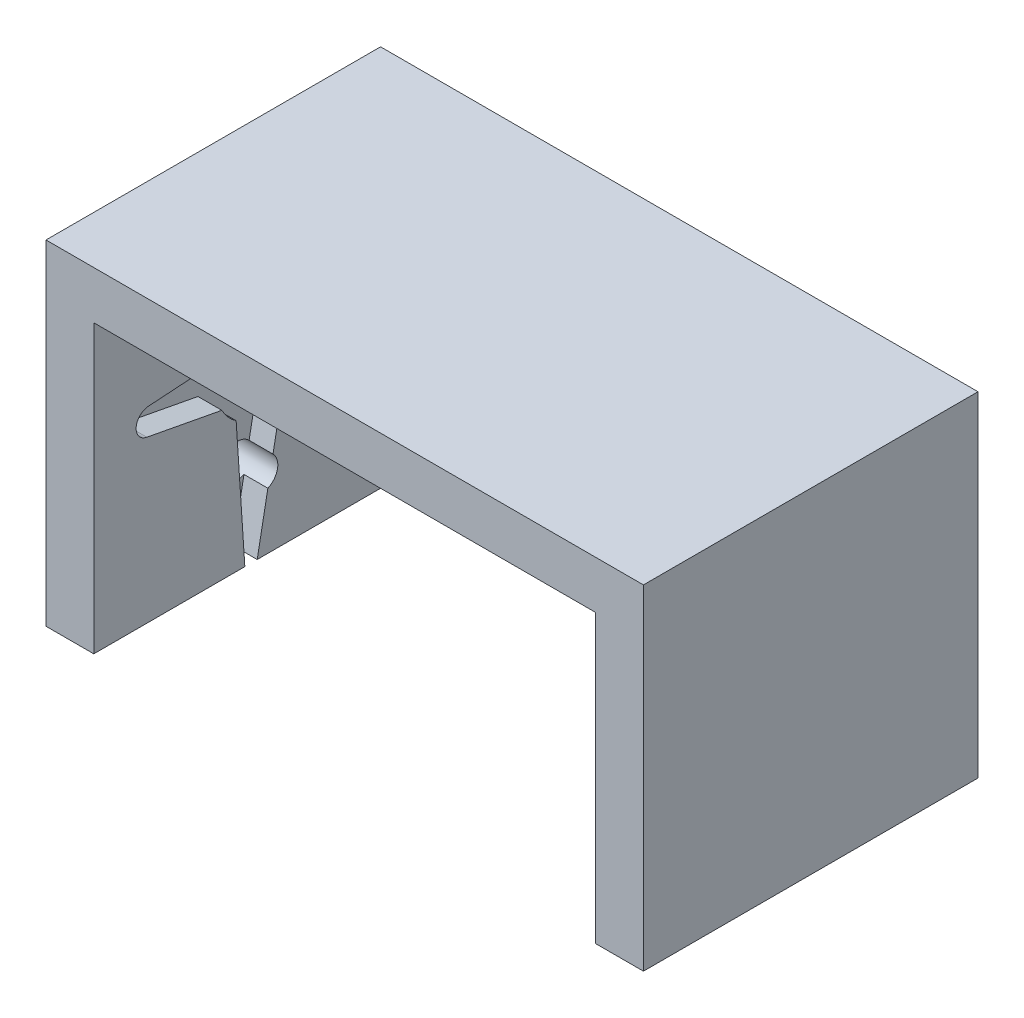
SolidWorks part; units mm, degrees
ref_plane "Front Plane" through (0, 0, 0) normal (0, 0, 1) x (1, 0, 0)
ref_plane "Top Plane" through (0, 0, 0) normal (0, 1, 0) x (1, 0, 0)
ref_plane "Right Plane" through (0, 0, 0) normal (1, 0, 0) x (0, 0, -1)
sketch "Sketch2" plane through (0, 0, 0) normal (0, 1, 0) x (1, 0, 0)
  line L1 (-62.5, 35) -> (62.5, 35)
  line L2 (-62.5, 35) -> (-62.5, -35)
  line L3 (-62.5, -35) -> (62.5, -35)
  line L4 (62.5, 35) -> (62.5, -35)
  line L5 (-62.5, 35) -> (62.5, -35) construction
  line L6 (-62.5, -35) -> (62.5, 35) construction
  point P0 (0, 0)
  dimension "D1" = 70
  dimension "D2" = 125
extrude "Boss-Extrude1" add sketch "Sketch2" along normal blind 10
sketch "Sketch3" plane through (0, 0, 0) normal (0, -1, 0) x (1, 0, 0)
  line L0 (62.5, -35) -> (-62.5, -35) construction
  line L1 (-62.5, 35) -> (-52.5, 35)
  line L2 (-62.5, 35) -> (-62.5, -35)
  line L3 (-62.5, -35) -> (-52.5, -35)
  line L4 (-52.5, 35) -> (-52.5, -35)
  line L6 (62.5, 35) -> (52.5, 35)
  line L7 (62.5, 35) -> (62.5, -35)
  line L8 (62.5, -35) -> (52.5, -35)
  line L9 (52.5, 35) -> (52.5, -35)
  dimension "D1" = 10
  dimension "D2" = 10
extrude "Boss-Extrude2" add sketch "Sketch3" along normal blind 60
sketch "Sketch4" plane through (-52.5, 0, 0) normal (1, 0, 0) x (0, 0, -1)
  line L0 (1.2885, -48.9065) -> (4.2627, -33.2093) construction
  line L1 (-0.8134, -60) -> (4.2627, -33.2093)
  line L2 (8.2093, -20.7373) -> (23.9065, -23.7115) construction
  line L3 (4.1574, -1.4225) -> (5.22, -17.3637) construction
  line L4 (35, 0) -> (-35, 0)
  line L5 (-35, 0) -> (-35, -60)
  line L6 (-35, -60) -> (35, -60)
  line L7 (35, -60) -> (35, 0)
  line L8 (4.0625, 0) -> (-1.0813, 0)
  line L10 (-3.3959, -60) -> (-0.8134, -60)
  line L12 (-4.2627, -16.7907) -> (-1.2885, -1.0935) construction
  line L13 (-23.5775, -20.8426) -> (-7.6363, -19.78) construction
  line L14 (-8.2093, -29.2627) -> (-23.9065, -26.2885) construction
  line L15 (23.5775, -29.1574) -> (7.6363, -30.22) construction
  line L16 (4.2627, -33.2093) -> (1.2885, -48.9065) construction
  line L17 (-5.22, -32.6363) -> (-4.1574, -48.5775) construction
  line L18 (8.2093, -20.7373) -> (23.9065, -23.7115)
  line L19 (4.0625, 0) -> (5.22, -17.3637)
  line L20 (-4.2627, -16.7907) -> (-1.0813, 0)
  line L21 (-23.5775, -20.8426) -> (-7.6363, -19.78)
  line L22 (-8.2093, -29.2627) -> (-23.9065, -26.2885)
  line L23 (23.5775, -29.1574) -> (7.6363, -30.22)
  line L24 (4.2627, -33.2093) -> (-0.8134, -60)
  line L25 (-5.22, -32.6363) -> (-3.3959, -60)
  line L26 (35, -60) -> (-35, -60) construction
  line L27 (35, 0) -> (-35, 0) construction
  arc A0 (8.2093, -20.7373) -> (5.22, -17.3637) centre (0, -25) ccw construction
  arc A1 (-4.2627, -16.7907) -> (-7.6363, -19.78) centre (0, -25) ccw construction
  arc A2 (-23.5775, -20.8426) -> (-23.9065, -26.2885) centre (-23.3946, -23.5865) ccw construction
  arc A3 (-8.2093, -29.2627) -> (-5.22, -32.6363) centre (0, -25) ccw construction
  arc A4 (23.5775, -29.1574) -> (23.9065, -23.7115) centre (23.3946, -26.4135) ccw construction
  arc A5 (4.2627, -33.2093) -> (7.6363, -30.22) centre (0, -25) ccw construction
  arc A6 (8.2093, -20.7373) -> (5.22, -17.3637) centre (0, -25) ccw
  arc A7 (-4.2627, -16.7907) -> (-7.6363, -19.78) centre (0, -25) ccw
  arc A8 (-23.5775, -20.8426) -> (-23.9065, -26.2885) centre (-23.3946, -23.5865) ccw
  arc A9 (-8.2093, -29.2627) -> (-5.22, -32.6363) centre (0, -25) ccw
  arc A10 (23.5775, -29.1574) -> (23.9065, -23.7115) centre (23.3946, -26.4135) ccw
  arc A11 (4.2627, -33.2093) -> (7.6363, -30.22) centre (0, -25) ccw
  circle A13 centre (0, -45) radius 3.5
  circle A14 centre (0, -45) radius 3.5
  line M6 (35, 0) -> (-35, 0)
  line M8 (-35, -60) -> (35, -60)
  dimension "D1" = 0
  dimension "D2" = 0
extrude "Cut-Extrude1" cut sketch "Sketch4" against normal blind 5 contours L1 A11 L23 A10 L18 A6 L19 L20 A7 L21 A8 L22 A9 L25 A14 M6 M8
sketch "Sketch6" plane through (-62.5, 0, 0) normal (-1, 0, 0) x (0, 0, 1)
  circle A1 centre (0, -45) radius 3.5
  circle A2 centre (0, -45) radius 3.5
  dimension "D2" = 0
extrude "Cut-Extrude2" cut sketch "Sketch6" against normal blind 15
